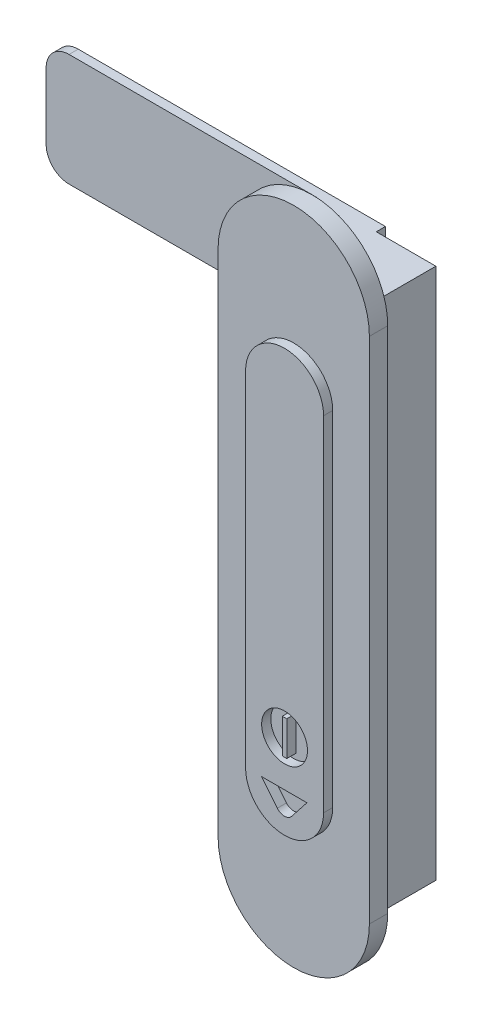
SolidWorks part; units mm, degrees
ref_plane "前视基准面" through (0, 0, 0) normal (0, 0, 1) x (1, 0, 0)
ref_plane "上视基准面" through (0, 0, 0) normal (0, 1, 0) x (1, 0, 0)
ref_plane "右视基准面" through (0, 0, 0) normal (1, 0, 0) x (0, 0, -1)
sketch "草图1" plane through (0, 0, 0) normal (0, 0, 1) x (1, 0, 0)
  line L0 (0, -55.5) -> (0, 55.5) construction
  line L1 (-16.5, -55.5) -> (-16.5, 55.5)
  line L2 (16.5, -55.5) -> (16.5, 55.5)
  arc A0 (-16.5, -55.5) -> (16.5, -55.5) centre (0, -55.5) ccw
  arc A1 (16.5, 55.5) -> (-16.5, 55.5) centre (0, 55.5) ccw
  point P2 (0, 0)
  point P8 (0, 72)
  point P9 (0, -72)
  dimension "D1" = 144
  dimension "33" = 33
extrude "凸台-拉伸1" add sketch "草图1" along normal blind 4
sketch "草图2" plane through (0, 0, 4) normal (0, 0, 1) x (1, 0, 0)
  line L0 (0, -37.5) -> (0, 37.5) construction
  line L1 (-8.5, -37.5) -> (-8.5, 37.5)
  line L2 (8.5, -37.5) -> (8.5, 37.5)
  arc A0 (-8.5, -37.5) -> (8.5, -37.5) centre (0, -37.5) ccw
  arc A1 (8.5, 37.5) -> (-8.5, 37.5) centre (0, 37.5) ccw
  circle A2 centre (0, -27.5) radius 5
  point P2 (0, 0)
  dimension "D3" = 10
  dimension "D1" = 75
  dimension "D2" = 17
  dimension "D4" = 10
extrude "凸台-拉伸2" add sketch "草图2" along normal blind 2
sketch "草图3" plane through (0, 0, 4) normal (0, 0, 1) x (1, 0, 0)
  line L1 (-0.4864, -23.744) -> (0.4864, -23.744)
  line L2 (-0.4864, -23.744) -> (-0.4864, -31.256)
  line L3 (-0.4864, -31.256) -> (0.4864, -31.256)
  line L4 (0.4864, -23.744) -> (0.4864, -31.256)
  line L5 (-0.4864, -23.744) -> (0.4864, -31.256) construction
  line L6 (-0.4864, -31.256) -> (0.4864, -23.744) construction
  point P0 (0, -27.5)
extrude "凸台-拉伸3" add sketch "草图3" along normal blind 2
sketch "草图4" plane through (0, 0, 6) normal (0, 0, 1) x (1, 0, 0)
  line L0 (0, -32.5) -> (0, -43.6138) construction
  line L1 (0, -43.6138) -> (4.8794, -37.4041)
  line L2 (4.8794, -37.4041) -> (-5, -37.4041)
  line L3 (-5, -37.4041) -> (0, -43.6138)
  circle A0 centre (0, -27.5) radius 5 construction
  point P6 (0, 0)
  point P9 (0, 0)
extrude "切除-拉伸1" cut sketch "草图4" against normal blind 2
fillet "圆角1" radius 2 1 edges at (0, -43.6138, 5)
sketch "草图5" plane through (0, 0, 0) normal (0, 0, -1) x (-1, 0, 0)
  line L1 (-13, -58) -> (13, -58)
  line L2 (-13, -58) -> (-13, 58)
  line L3 (-13, 58) -> (13, 58)
  line L4 (13, -58) -> (13, 58)
  line L5 (-13, -58) -> (13, 58) construction
  line L6 (-13, 58) -> (13, -58) construction
  point P0 (0, 0)
  dimension "D1" = 26
  dimension "D2" = 116
extrude "凸台-拉伸4" add sketch "草图5" along normal blind 14
sketch "草图6" plane through (0, 0, -14) normal (0, 0, -1) x (-1, 0, 0)
  line L0 (13, 58) -> (-13, 58) construction
  line L1 (0, 58) -> (67, 58)
  line L2 (0, 58) -> (0, 33.5)
  line L3 (0, 33.5) -> (67, 33.5)
  line L4 (72, 53) -> (72, 38.5)
  arc A0 (67, 33.5) -> (72, 38.5) centre (67, 38.5) ccw
  arc A1 (72, 53) -> (67, 58) centre (67, 53) ccw
  dimension "D3" = 5
  dimension "D1" = 72
  dimension "D2" = 24.5
extrude "凸台-拉伸5" add sketch "草图6" along normal blind 2
